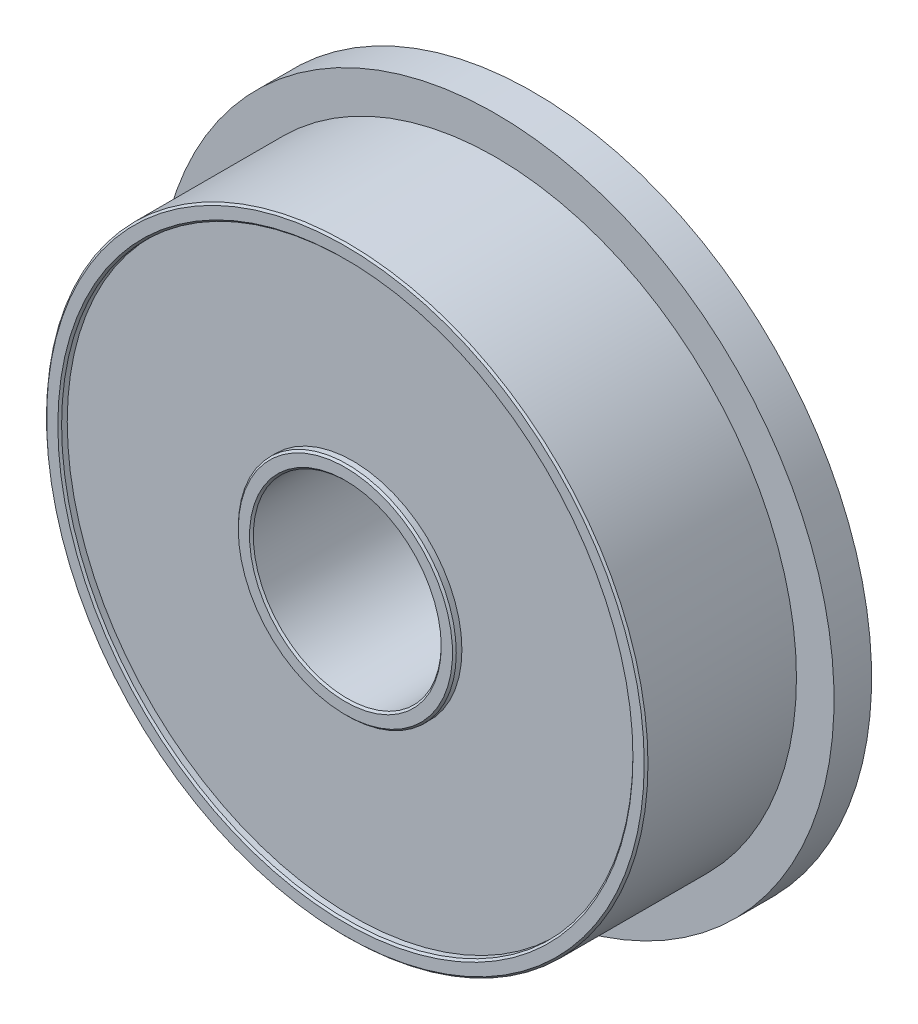
SolidWorks part; units mm, degrees
material "普通碳钢"
ref_plane "前视基准面" through (0, 0, 0) normal (0, 0, 1) x (1, 0, 0)
ref_plane "上视基准面" through (0, 0, 0) normal (0, 1, 0) x (1, 0, 0)
ref_plane "右视基准面" through (0, 0, 0) normal (1, 0, 0) x (0, 0, -1)
sketch "草图1" plane through (0, 0, 0) normal (0, 0, 1) x (1, 0, 0)
  circle A0 centre (0, 0) radius 2.5
  circle A1 centre (0, 0) radius 8
  dimension "D1" = 5
  dimension "D2" = 16
extrude "凸台-拉伸1" add sketch "草图1" along normal mid plane 5
sketch "草图3" plane through (0, 0, -2.5) normal (0, 0, -1) x (-1, 0, 0)
  circle A0 centre (0, 0) radius 2.5 construction
  circle A1 centre (0, 0) radius 2.5
  circle A2 centre (0, 0) radius 9
  dimension "D1" = 18
extrude "凸台-拉伸2" add sketch "草图3" against normal blind 1
sketch "草图4" plane through (0, 0, 2.5) normal (0, 0, 1) x (1, 0, 0)
  circle A2 centre (0, 0) radius 2.9
  circle A3 centre (0, 0) radius 2.9
  circle A6 centre (0, 0) radius 7.6
  circle A7 centre (0, 0) radius 7.6
  dimension "D1" = 0.4
  dimension "D2" = 0.4
extrude "切除-拉伸1" cut sketch "草图4" against normal blind 0.2
mirror "镜向1" about plane through (0, 0, 0) normal (0, 0, 1) of "切除-拉伸1"
chamfer "倒角1" distance 0.05 angle 45 7 edges at (2.5, 0, -2.5) (2.9, 0, -2.5) (2.9, 0, 2.5) (2.5, 0, 2.5) (8, 0, 2.5) (7.6, 0, 2.5) (7.6, 0, -2.5)
move or copy body "实体-移动/复制3" [suppressed] bodies to move or copy 109
move or copy body "实体-移动/复制1" [suppressed] bodies to move or copy 109
move or copy body "实体-移动/复制2" [suppressed] bodies to move or copy 109
equation "\"内径\"= 2"
equation "\"外径\"= 5"
equation "\"法兰外径\"= 6.1"
equation "\"宽度\"= 2.3"
equation "\"法兰宽度\"= 0.6"
equation "\"D1@草图1\"=\"内径\""
equation "\"D2@草图1\"=\"外径\""
equation "\"D1@草图3\"=\"法兰外径\""
equation "\"D1@凸台-拉伸1\"=\"宽度\""
equation "\"D1@凸台-拉伸2\"=\"法兰宽度\""
